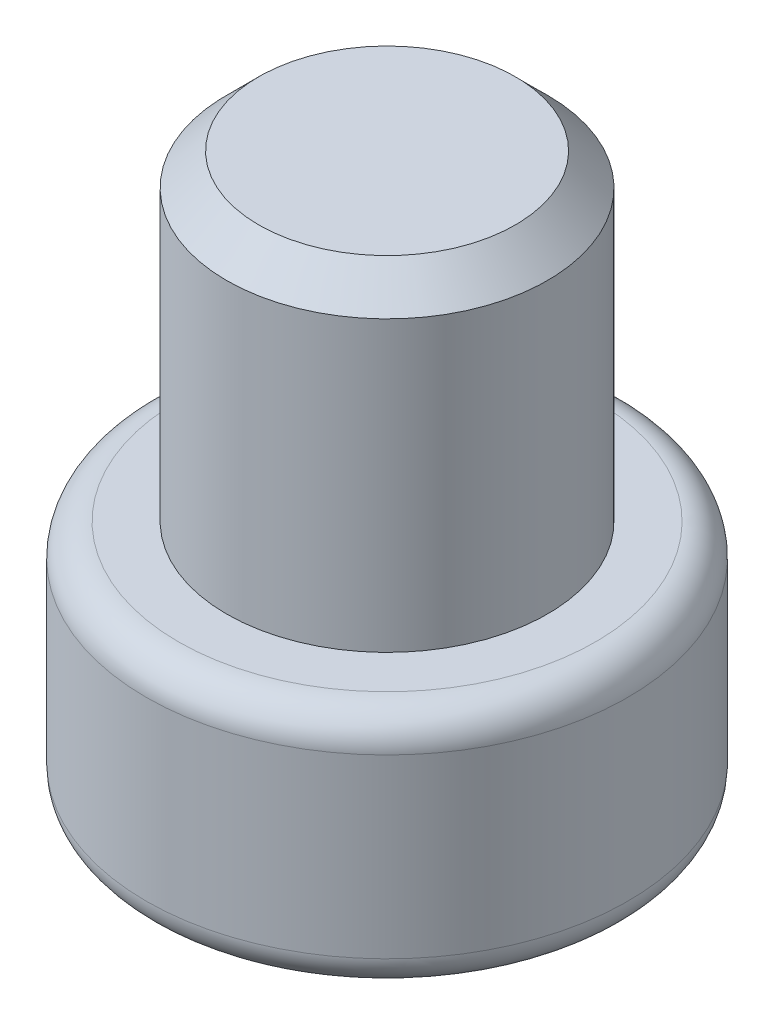
SolidWorks part; units mm, degrees
ref_plane "Front Plane" through (0, 0, 0) normal (0, 0, 1) x (1, 0, 0)
ref_plane "Top Plane" through (0, 0, 0) normal (0, 1, 0) x (1, 0, 0)
ref_plane "Right Plane" through (0, 0, 0) normal (1, 0, 0) x (0, 0, -1)
sketch "Sketch1" plane through (0, 0, 0) normal (0, 1, 0) x (1, 0, 0)
  circle A0 centre (0, 0) radius 10.5
  circle A1 centre (0, 0) radius 15
  dimension "D1" = 21
  dimension "D2" = 30
extrude "Boss-Extrude1" add sketch "Sketch1" along normal blind 10
sketch "Sketch2" plane through (0, 10, 0) normal (0, 1, 0) x (1, 0, 0)
  circle A1 centre (0, 0) radius 15
  circle A2 centre (0, 0) radius 15
  dimension "D1" = 0
extrude "Boss-Extrude2" add sketch "Sketch2" along normal blind 5
sketch "Sketch3" plane through (0, 15, 0) normal (0, 1, 0) x (1, 0, 0)
  circle A0 centre (0, 0) radius 10
  dimension "D1" = 20
extrude "Boss-Extrude3" add sketch "Sketch3" along normal blind 20
chamfer "Chamfer2" distance 2 angle 45 1 edges at (0, 35, 10)
fillet "Fillet1" radius 2 2 edges at (0, 0, 15) (0, 15, 15)
